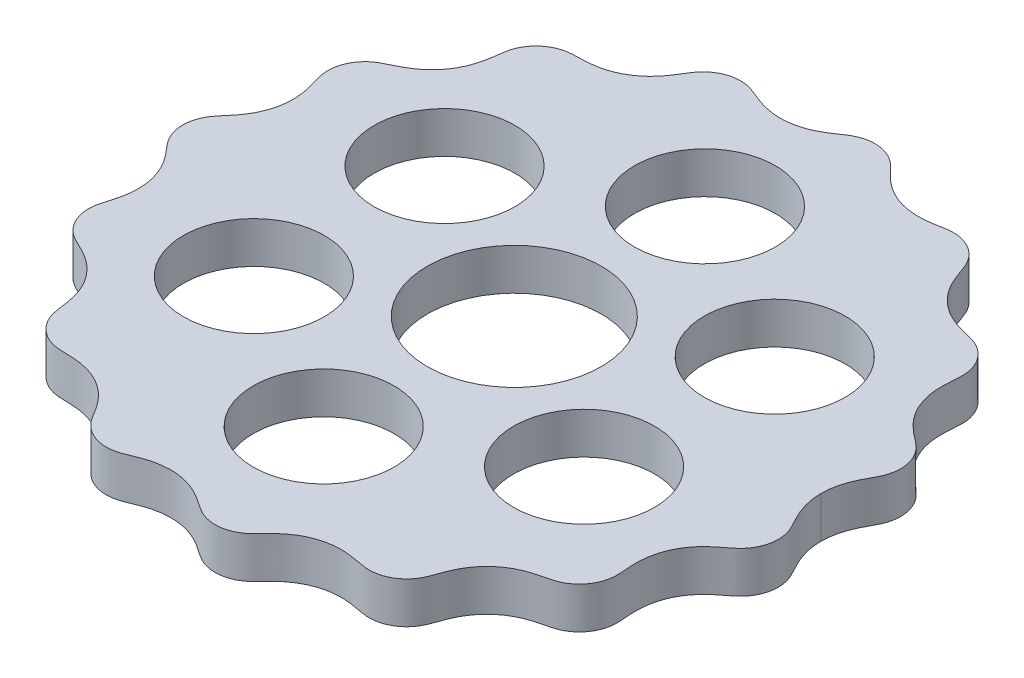
SolidWorks part; units mm, degrees
ref_plane "Front Plane" through (0, 0, 0) normal (0, 0, 1) x (1, 0, 0)
ref_plane "Top Plane" through (0, 0, 0) normal (0, 1, 0) x (1, 0, 0)
ref_plane "Right Plane" through (0, 0, 0) normal (1, 0, 0) x (0, 0, -1)
sketch "Sketch1" plane through (0, 0, 0) normal (0, 1, 0) x (1, 0, 0)
  circle A0 centre (0, 0) radius 10.5
  circle A1 centre (0, 0) radius 23 construction
  circle A2 centre (0, 23) radius 8.5
  circle A3 centre (19.9186, 11.5) radius 8.5
  circle A4 centre (19.9186, -11.5) radius 8.5
  circle A5 centre (0, -23) radius 8.5
  circle A6 centre (-19.9186, -11.5) radius 8.5
  circle A7 centre (-19.9186, 11.5) radius 8.5
  spline S0 degree 4 poles (38.6756, 9.5405) (38.7869, 9.3354) (38.9807, 8.9098) (39.18, 8.2438) (39.2638, 7.3275) (39.17, 6.4698) (38.9321, 5.7015) (38.5995, 5.0253) (38.2553, 4.4109) (37.9563, 3.8443) (37.7129, 3.322) (37.522, 2.8468) (37.3939, 2.4766) (37.2981, 2.1548) (37.2278, 1.884) (37.1776, 1.6659) (37.1334, 1.4465) (37.0953, 1.226) (37.0635, 1.0045) (37.0411, 0.8091) (37.0259, 0.6435) (37.0159, 0.5055) (37.0095, 0.392) (37.0035, 0.2438) (36.9999, 0.079) (36.9994, -0.0361) (37.0025, -0.21) (37.0079, -0.366) (37.0181, -0.5474) (37.0358, -0.7626) (37.0623, -1.0007) (37.0996, -1.2541) (37.1417, -1.4901) (37.1867, -1.7077) (37.276, -2.0862) (37.4326, -2.6197) (37.6503, -3.1917) (37.9334, -3.7956) (38.206, -4.3157) (38.4505, -4.7606) (38.7069, -5.2352) (38.9418, -5.7567) (39.1379, -6.3788) (39.248, -7.1039) (39.2286, -7.94) (39.0193, -8.8558) (38.5776, -9.8235) (37.821, -10.7544) (36.8481, -11.435) (35.9255, -12.1707) (35.1552, -12.9314) (34.5438, -13.6951) (33.8952, -14.742) (33.4284, -15.8904) (33.1613, -17.1041) (33.0908, -18.2767) (33.1179, -19.1348) (33.1846, -19.9227) (33.2426, -20.6446) (33.2196, -21.4379) (33.0363, -22.2817) (32.6622, -23.1285) (32.0787, -23.9264) (31.2705, -24.6475) (30.2129, -25.1958) (29.0562, -25.4259) (27.9212, -25.7148) (26.9129, -26.088) (26.0467, -26.5265) (25.2315, -27.0702) (24.4863, -27.7162) (23.8232, -28.4568) (23.2548, -29.2804) (22.819, -30.1054) (22.4892, -30.9045) (22.2262, -31.656) (21.9863, -32.3444) (21.6457, -33.0672) (21.1369, -33.7721) (20.4446, -34.4052) (19.5735, -34.9081) (18.6791, -35.1912) (17.8142, -35.2793) (17.018, -35.2129) (16.3018, -35.0765) (15.5195, -34.9284) (14.6625, -34.8147) (13.4804, -34.7697) (12.2411, -34.9196) (11.052, -35.2755) (9.9494, -35.8202) (9.1364, -36.3513) (8.3091, -37.0378) (7.4914, -37.8764) (6.7137, -38.763) (5.7101, -39.4048) (4.6815, -39.7442) (3.6987, -39.8506) (2.7784, -39.7512) (1.9559, -39.488) (1.2575, -39.1113) (0.6613, -38.7001) (0.0122, -38.2484) (-0.7173, -37.7958) (-1.768, -37.2706) (-2.9527, -36.8951) (-4.1807, -36.7251) (-5.4116, -36.7634) (-6.3787, -36.9109) (-7.4226, -37.1978) (-8.5211, -37.6287) (-9.5969, -38.1313) (-10.7814, -38.3206) (-11.8653, -38.2177) (-12.81, -37.9179) (-13.7654, -37.3701) (-14.6397, -36.51) (-15.225, -35.4471) (-15.8752, -34.4321) (-16.7227, -33.382) (-17.6452, -32.5494) (-18.6953, -31.8812) (-19.8393, -31.4031) (-20.7931, -31.1347) (-21.8817, -30.9645) (-23.0854, -30.9087) (-24.2988, -30.9334) (-25.4807, -30.6062) (-26.4329, -30.0527) (-27.1648, -29.3844) (-27.7959, -28.4973) (-28.2242, -27.3768) (-28.3269, -26.1938) (-28.503, -25.027) (-28.7764, -23.9796) (-29.1322, -23.0683) (-29.7145, -21.9831) (-30.4757, -21.0047) (-31.3933, -20.1664) (-32.3735, -19.5191) (-33.1302, -19.1136) (-33.8459, -18.7774) (-34.5001, -18.4667) (-35.1756, -18.0501) (-35.8147, -17.4694) (-36.361, -16.7221) (-36.7603, -15.8178) (-36.9806, -14.7573) (-36.9266, -13.5673) (-36.5476, -12.4504) (-36.2302, -11.323) (-36.0493, -10.2632) (-35.996, -9.2938) (-36.0592, -8.316) (-36.2461, -7.3476) (-36.5559, -6.4031) (-36.985, -5.499) (-37.4816, -4.7092) (-38.0086, -4.024) (-38.5281, -3.4205) (-39.0041, -2.8683) (-39.353, -2.3666) (-39.5782, -1.9309) (-39.7176, -1.5888) (-39.7983, -1.3525) (-39.8659, -1.1123) (-39.9132, -0.899) (-39.9453, -0.714) (-39.9664, -0.5608) (-39.98, -0.4381) (-39.9901, -0.3108) (-39.9969, -0.1759) (-40.0009, -0.0264) (-39.9998, 0.101) (-39.9919, 0.3019) (-39.9779, 0.461) (-39.962, 0.5936) (-39.9468, 0.7) (-39.9245, 0.8336) (-39.8928, 0.9931) (-39.8356, 1.2296) (-39.7321, 1.5628) (-39.5698, 1.9581) (-39.3263, 2.4015) (-39.0212, 2.8342) (-38.6301, 3.3062) (-38.1713, 3.8306) (-37.748, 4.3543) (-37.3751, 4.8861) (-37.0367, 5.4401) (-36.6355, 6.2077) (-36.2169, 7.3272) (-36.0304, 8.4018) (-36.0089, 9.2689) (-36.0283, 9.7011) knots 0 0 0 0 0 0.006139 0.012278 0.018165 0.024053 0.028687 0.033322 0.037957 0.042591 0.045535 0.048479 0.051424 0.052896 0.054368 0.05584 0.057312 0.058784 0.060256 0.061728 0.062464 0.0632 0.063936 0.064672 0.066144 0.067103 0.068061 0.06902 0.069978 0.071895 0.073812 0.075274 0.076735 0.078197 0.079659 0.085505 0.091352 0.094275 0.097198 0.100954 0.104711 0.108467 0.112223 0.11807 0.123916 0.130339 0.136761 0.145879 0.154997 0.161421 0.167846 0.17427 0.180694 0.193737 0.200258 0.206779 0.211542 0.216304 0.221067 0.225829 0.232349 0.238869 0.245245 0.251622 0.260677 0.269731 0.27611 0.282488 0.288866 0.295244 0.301811 0.308378 0.314945 0.321512 0.326307 0.331102 0.335897 0.340691 0.347256 0.353821 0.360386 0.366951 0.371745 0.37654 0.381335 0.38613 0.392697 0.399264 0.412398 0.418776 0.425154 0.431532 0.437911 0.446965 0.45602 0.462396 0.468773 0.475293 0.481813 0.486575 0.491338 0.4961 0.500863 0.507384 0.513905 0.526948 0.533372 0.539796 0.54622 0.552645 0.561763 0.570881 0.577303 0.583726 0.59023 0.596734 0.606103 0.615471 0.621978 0.628484 0.641498 0.648004 0.654511 0.661018 0.667524 0.676893 0.686261 0.692765 0.699269 0.705692 0.712114 0.721232 0.730351 0.736775 0.743199 0.749623 0.756047 0.76909 0.775611 0.782133 0.786895 0.791658 0.79642 0.801182 0.807702 0.814222 0.820599 0.826976 0.83603 0.845085 0.851463 0.857841 0.864219 0.870597 0.877164 0.883732 0.890299 0.896866 0.90166 0.906455 0.91125 0.916045 0.917686 0.919327 0.920968 0.922609 0.924251 0.925071 0.925892 0.926712 0.927533 0.928354 0.929174 0.930597 0.93202 0.932732 0.933444 0.934155 0.934867 0.93629 0.937713 0.940559 0.944036 0.947513 0.950991 0.954468 0.960159 0.965851 0.968697 0.971542 0.977234 0.988617 1 1 1 1 1 construction
  spline S1 degree 4 poles (37, 0) (37, -0.0314) (37.0005, -0.095) (37.0025, -0.21) (37.0079, -0.366) (37.0181, -0.5474) (37.0358, -0.7626) (37.0623, -1.0007) (37.0996, -1.2541) (37.1417, -1.4901) (37.1867, -1.7077) (37.276, -2.0862) (37.4326, -2.6197) (37.6503, -3.1917) (37.9334, -3.7956) (38.206, -4.3157) (38.4505, -4.7606) (38.7069, -5.2352) (38.9418, -5.7567) (39.1379, -6.3788) (39.248, -7.1039) (39.2286, -7.94) (39.0193, -8.8558) (38.5776, -9.8235) (37.821, -10.7544) (36.8481, -11.435) (35.9255, -12.1707) (35.1552, -12.9314) (34.5438, -13.6951) (33.8952, -14.742) (33.4284, -15.8904) (33.1613, -17.1041) (33.0908, -18.2767) (33.1179, -19.1348) (33.1846, -19.9227) (33.2426, -20.6446) (33.2196, -21.4379) (33.0363, -22.2817) (32.6622, -23.1285) (32.0787, -23.9264) (31.2705, -24.6475) (30.2129, -25.1958) (29.0562, -25.4259) (27.9212, -25.7148) (26.9129, -26.088) (26.0467, -26.5265) (25.2315, -27.0702) (24.4863, -27.7162) (23.8232, -28.4568) (23.2548, -29.2804) (22.819, -30.1054) (22.4892, -30.9045) (22.2262, -31.656) (21.9863, -32.3444) (21.6457, -33.0672) (21.1369, -33.7721) (20.4446, -34.4052) (19.5735, -34.9081) (18.6791, -35.1912) (17.8142, -35.2793) (17.018, -35.2129) (16.3018, -35.0765) (15.5195, -34.9284) (14.6625, -34.8147) (13.4804, -34.7697) (12.2411, -34.9196) (11.052, -35.2755) (9.9494, -35.8202) (9.1364, -36.3513) (8.3091, -37.0378) (7.4914, -37.8764) (6.7137, -38.763) (5.7101, -39.4048) (4.6815, -39.7442) (3.6987, -39.8506) (2.7784, -39.7512) (1.9559, -39.488) (1.2575, -39.1113) (0.6613, -38.7001) (0.0122, -38.2484) (-0.7173, -37.7958) (-1.768, -37.2706) (-2.9527, -36.8951) (-4.1807, -36.7251) (-5.4116, -36.7634) (-6.3787, -36.9109) (-7.4226, -37.1978) (-8.5211, -37.6287) (-9.5969, -38.1313) (-10.7814, -38.3206) (-11.8653, -38.2177) (-12.81, -37.9179) (-13.7654, -37.3701) (-14.6397, -36.51) (-15.225, -35.4471) (-15.8752, -34.4321) (-16.7227, -33.382) (-17.6452, -32.5494) (-18.6953, -31.8812) (-19.8393, -31.4031) (-20.7931, -31.1347) (-21.8817, -30.9645) (-23.0854, -30.9087) (-24.2988, -30.9334) (-25.4807, -30.6062) (-26.4329, -30.0527) (-27.1648, -29.3844) (-27.7959, -28.4973) (-28.2242, -27.3768) (-28.3269, -26.1938) (-28.503, -25.027) (-28.7764, -23.9796) (-29.1322, -23.0683) (-29.7145, -21.9831) (-30.4757, -21.0047) (-31.3933, -20.1664) (-32.3735, -19.5191) (-33.1302, -19.1136) (-33.8459, -18.7774) (-34.5001, -18.4667) (-35.1756, -18.0501) (-35.8147, -17.4694) (-36.361, -16.7221) (-36.7603, -15.8178) (-36.9806, -14.7573) (-36.9266, -13.5673) (-36.5476, -12.4504) (-36.2302, -11.323) (-36.0493, -10.2632) (-35.996, -9.2938) (-36.0592, -8.316) (-36.2461, -7.3476) (-36.5559, -6.4031) (-36.985, -5.499) (-37.4816, -4.7092) (-38.0086, -4.024) (-38.5281, -3.4205) (-39.0041, -2.8683) (-39.353, -2.3666) (-39.5782, -1.9309) (-39.7176, -1.5888) (-39.7983, -1.3525) (-39.8659, -1.1123) (-39.9132, -0.899) (-39.9453, -0.714) (-39.9664, -0.5608) (-39.98, -0.4381) (-39.9901, -0.3108) (-39.9969, -0.1759) (-39.9994, -0.0812) (-40, -0.0269) (-40, 0) knots 0.066144 0.066144 0.066144 0.066144 0.066144 0.067103 0.068061 0.06902 0.069978 0.071895 0.073812 0.075274 0.076735 0.078197 0.079659 0.085505 0.091352 0.094275 0.097198 0.100954 0.104711 0.108467 0.112223 0.11807 0.123916 0.130339 0.136761 0.145879 0.154997 0.161421 0.167846 0.17427 0.180694 0.193737 0.200258 0.206779 0.211542 0.216304 0.221067 0.225829 0.232349 0.238869 0.245245 0.251622 0.260677 0.269731 0.27611 0.282488 0.288866 0.295244 0.301811 0.308378 0.314945 0.321512 0.326307 0.331102 0.335897 0.340691 0.347256 0.353821 0.360386 0.366951 0.371745 0.37654 0.381335 0.38613 0.392697 0.399264 0.412398 0.418776 0.425154 0.431532 0.437911 0.446965 0.45602 0.462396 0.468773 0.475293 0.481813 0.486575 0.491338 0.4961 0.500863 0.507384 0.513905 0.526948 0.533372 0.539796 0.54622 0.552645 0.561763 0.570881 0.577303 0.583726 0.59023 0.596734 0.606103 0.615471 0.621978 0.628484 0.641498 0.648004 0.654511 0.661018 0.667524 0.676893 0.686261 0.692765 0.699269 0.705692 0.712114 0.721232 0.730351 0.736775 0.743199 0.749623 0.756047 0.76909 0.775611 0.782133 0.786895 0.791658 0.79642 0.801182 0.807702 0.814222 0.820599 0.826976 0.83603 0.845085 0.851463 0.857841 0.864219 0.870597 0.877164 0.883732 0.890299 0.896866 0.90166 0.906455 0.91125 0.916045 0.917686 0.919327 0.920968 0.922609 0.924251 0.925071 0.925892 0.926712 0.927533 0.928354 0.929174 0.929174 0.929174 0.929174 0.929174
  spline S2 degree 4 poles (-36.0283, -9.7011) (-36.0089, -9.2689) (-36.025, -8.6185) (-36.1423, -7.7571) (-36.4452, -6.7165) (-36.7773, -5.9157) (-37.1923, -5.1548) (-37.6189, -4.528) (-38.0202, -4.0177) (-38.3849, -3.5864) (-38.6992, -3.2229) (-38.979, -2.8851) (-39.2119, -2.5638) (-39.3869, -2.2834) (-39.514, -2.0514) (-39.6452, -1.7744) (-39.7518, -1.4995) (-39.8356, -1.2297) (-39.8991, -0.9667) (-39.9398, -0.7534) (-39.9703, -0.5412) (-39.9907, -0.329) (-39.9998, -0.1024) (-40.0009, 0.0274) (-39.9969, 0.174) (-39.9901, 0.3085) (-39.98, 0.4378) (-39.9664, 0.5616) (-39.9495, 0.6838) (-39.9292, 0.8064) (-39.9056, 0.9291) (-39.8785, 1.0511) (-39.8405, 1.2024) (-39.7882, 1.382) (-39.7175, 1.5887) (-39.6127, 1.8466) (-39.4787, 2.1231) (-39.3107, 2.4141) (-39.1049, 2.7153) (-38.8813, 3.0032) (-38.6471, 3.2825) (-38.3498, 3.6277) (-37.9529, 4.0962) (-37.4817, 4.7093) (-36.9849, 5.4989) (-36.556, 6.4033) (-36.1702, 7.5783) (-35.9868, 8.7988) (-36.0091, 10.0244) (-36.2006, 11.152) (-36.4085, 11.955) (-36.6307, 12.6803) (-36.8216, 13.3417) (-36.9923, 14.3318) (-36.9049, 15.4222) (-36.5044, 16.5243) (-35.815, 17.4697) (-35.1754, 18.05) (-34.5001, 18.4666) (-33.846, 18.7777) (-32.9056, 19.2181) (-31.7252, 19.8872) (-30.4396, 20.9666) (-29.2852, 22.5861) (-28.6866, 24.1372) (-28.4341, 25.439) (-28.3116, 26.4395) (-28.2186, 27.1266) (-28.0361, 27.8709) (-27.6947, 28.6385) (-27.1647, 29.385) (-26.4334, 30.0526) (-25.6346, 30.5161) (-24.8231, 30.7888) (-24.0469, 30.8992) (-23.3347, 30.9203) (-22.3064, 30.9378) (-20.9635, 31.0586) (-19.3449, 31.507) (-17.6134, 32.5067) (-16.4158, 33.6842) (-15.6397, 34.7868) (-15.1104, 35.6686) (-14.7361, 36.2748) (-14.2524, 36.8918) (-13.6104, 37.4583) (-12.8096, 37.9183) (-11.8658, 38.2178) (-10.9543, 38.3035) (-10.1188, 38.2154) (-9.383, 38.0014) (-8.7414, 37.7383) (-7.8138, 37.3442) (-6.5601, 36.912) (-4.9175, 36.6548) (-2.9379, 36.8448) (-1.3603, 37.4184) (-0.1906, 38.1061) (0.661, 38.7003) (1.2575, 39.1113) (1.9559, 39.4878) (2.7783, 39.7515) (3.9418, 39.8759) (5.0965, 39.6717) (6.0845, 39.2022) (6.8565, 38.5593) (7.3339, 38.0633) (7.8509, 37.5082) (8.4424, 36.9267) (9.3231, 36.1969) (10.5884, 35.4356) (11.9992, 34.9487) (13.4803, 34.7698) (14.6625, 34.8147) (15.5194, 34.9284) (16.3018, 35.0765) (17.0179, 35.2129) (17.8142, 35.2793) (18.6791, 35.1911) (19.5735, 34.9082) (20.4445, 34.4052) (21.137, 33.7722) (21.5918, 33.1415) (21.8696, 32.5926) (22.0759, 32.0862) (22.2266, 31.6561) (22.3766, 31.2261) (22.5937, 30.6514) (22.8615, 30.0249) (23.2551, 29.2802) (23.8228, 28.4571) (24.6491, 27.5346) (25.8025, 26.6152) (27.2181, 25.9053) (28.8176, 25.4727) (30.4528, 25.1488) (31.6988, 24.3833) (32.5609, 23.3518) (33.0376, 22.2818) (33.2189, 21.4379) (33.243, 20.6446) (33.1848, 19.9227) (33.0963, 18.888) (33.0853, 17.5312) (33.3775, 15.8781) (34.2027, 14.0687) (35.2468, 12.7747) (36.2479, 11.9052) (37.0531, 11.2989) (37.6016, 10.8748) (38.155, 10.3445) (38.649, 9.665) (39.0305, 8.8328) (39.243, 7.8658) (39.2451, 6.9422) (39.0753, 6.1031) (38.7832, 5.3754) (38.4446, 4.7486) (38.1266, 4.173) (37.8549, 3.634) (37.633, 3.1317) (37.4786, 2.7272) (37.3626, 2.3747) (37.2774, 2.0775) (37.2164, 1.8379) (37.1626, 1.5964) (37.1163, 1.3536) (37.0774, 1.1094) (37.0502, 0.8937) (37.0316, 0.7109) (37.0194, 0.5584) (37.0116, 0.4331) (37.0042, 0.2696) (36.9994, 0.0658) (36.9993, -0.087) (37.0071, -0.3742) (37.0226, -0.616) (37.0458, -0.8587) (37.0767, -1.1038) (37.1247, -1.4076) (37.1852, -1.7092) (37.2578, -2.0082) (37.3591, -2.3632) (37.4739, -2.7141) (37.627, -3.1167) (37.8469, -3.6171) (38.1165, -4.154) (38.4326, -4.7273) (38.7709, -5.3508) (39.0661, -6.0733) (39.2414, -6.9072) (39.2472, -7.9128) (39.0566, -8.7198) (38.8323, -9.2517) (38.6756, -9.5405) knots 0 0 0 0 0 0.011383 0.017074 0.022766 0.028458 0.034149 0.039841 0.042687 0.045532 0.049009 0.052487 0.054225 0.055964 0.057702 0.059441 0.062287 0.06371 0.065133 0.066556 0.06798 0.069403 0.070826 0.071646 0.072467 0.073288 0.074108 0.074929 0.075749 0.07657 0.077391 0.078211 0.079032 0.080673 0.082314 0.083955 0.086353 0.08875 0.091148 0.093545 0.095942 0.09834 0.103134 0.109701 0.116269 0.122836 0.129403 0.142159 0.148537 0.154915 0.159443 0.16397 0.168497 0.173024 0.185778 0.192298 0.198818 0.20358 0.208342 0.213105 0.217867 0.23091 0.243953 0.256801 0.269649 0.274209 0.278768 0.283327 0.287886 0.294308 0.300731 0.307235 0.313739 0.318423 0.323107 0.327792 0.332476 0.345489 0.358502 0.371516 0.384529 0.389213 0.393897 0.398582 0.403266 0.40977 0.416274 0.422697 0.429119 0.433678 0.438237 0.442796 0.447355 0.460204 0.473052 0.486095 0.499137 0.5039 0.508662 0.513425 0.518187 0.524707 0.531227 0.54398 0.548508 0.553035 0.557562 0.56209 0.568468 0.574846 0.587602 0.600736 0.607303 0.613871 0.618665 0.62346 0.628255 0.633049 0.639614 0.646179 0.652744 0.659309 0.664104 0.666501 0.668898 0.673693 0.67609 0.678488 0.685055 0.691622 0.698189 0.704756 0.717512 0.730269 0.739323 0.748378 0.761131 0.767651 0.774171 0.778933 0.783696 0.788458 0.793221 0.806263 0.819306 0.832154 0.845003 0.849562 0.854121 0.85868 0.863239 0.869662 0.876084 0.882588 0.889092 0.893777 0.898461 0.903145 0.907829 0.911083 0.914336 0.917589 0.919216 0.920842 0.922469 0.924096 0.925722 0.927349 0.928976 0.929789 0.930602 0.931416 0.932229 0.933856 0.935474 0.937093 0.938711 0.94033 0.941948 0.943567 0.946804 0.948422 0.950041 0.953278 0.956515 0.959752 0.964416 0.96908 0.973744 0.978408 0.984882 0.991355 1 1 1 1 1 construction
  spline S3 degree 4 poles (-40, 0) (-40, 0.0269) (-39.9994, 0.0811) (-39.9969, 0.174) (-39.9901, 0.3085) (-39.98, 0.4378) (-39.9664, 0.5616) (-39.9495, 0.6838) (-39.9292, 0.8064) (-39.9056, 0.9291) (-39.8785, 1.0511) (-39.8405, 1.2024) (-39.7882, 1.382) (-39.7175, 1.5887) (-39.6127, 1.8466) (-39.4787, 2.1231) (-39.3107, 2.4141) (-39.1049, 2.7153) (-38.8813, 3.0032) (-38.6471, 3.2825) (-38.3498, 3.6277) (-37.9529, 4.0962) (-37.4817, 4.7093) (-36.9849, 5.4989) (-36.556, 6.4033) (-36.1702, 7.5783) (-35.9868, 8.7988) (-36.0091, 10.0244) (-36.2006, 11.152) (-36.4085, 11.955) (-36.6307, 12.6803) (-36.8216, 13.3417) (-36.9923, 14.3318) (-36.9049, 15.4222) (-36.5044, 16.5243) (-35.815, 17.4697) (-35.1754, 18.05) (-34.5001, 18.4666) (-33.846, 18.7777) (-32.9056, 19.2181) (-31.7252, 19.8872) (-30.4396, 20.9666) (-29.2852, 22.5861) (-28.6866, 24.1372) (-28.4341, 25.439) (-28.3116, 26.4395) (-28.2186, 27.1266) (-28.0361, 27.8709) (-27.6947, 28.6385) (-27.1647, 29.385) (-26.4334, 30.0526) (-25.6346, 30.5161) (-24.8231, 30.7888) (-24.0469, 30.8992) (-23.3347, 30.9203) (-22.3064, 30.9378) (-20.9635, 31.0586) (-19.3449, 31.507) (-17.6134, 32.5067) (-16.4158, 33.6842) (-15.6397, 34.7868) (-15.1104, 35.6686) (-14.7361, 36.2748) (-14.2524, 36.8918) (-13.6104, 37.4583) (-12.8096, 37.9183) (-11.8658, 38.2178) (-10.9543, 38.3035) (-10.1188, 38.2154) (-9.383, 38.0014) (-8.7414, 37.7383) (-7.8138, 37.3442) (-6.5601, 36.912) (-4.9175, 36.6548) (-2.9379, 36.8448) (-1.3603, 37.4184) (-0.1906, 38.1061) (0.661, 38.7003) (1.2575, 39.1113) (1.9559, 39.4878) (2.7783, 39.7515) (3.9418, 39.8759) (5.0965, 39.6717) (6.0845, 39.2022) (6.8565, 38.5593) (7.3339, 38.0633) (7.8509, 37.5082) (8.4424, 36.9267) (9.3231, 36.1969) (10.5884, 35.4356) (11.9992, 34.9487) (13.4803, 34.7698) (14.6625, 34.8147) (15.5194, 34.9284) (16.3018, 35.0765) (17.0179, 35.2129) (17.8142, 35.2793) (18.6791, 35.1911) (19.5735, 34.9082) (20.4445, 34.4052) (21.137, 33.7722) (21.5918, 33.1415) (21.8696, 32.5926) (22.0759, 32.0862) (22.2266, 31.6561) (22.3766, 31.2261) (22.5937, 30.6514) (22.8615, 30.0249) (23.2551, 29.2802) (23.8228, 28.4571) (24.6491, 27.5346) (25.8025, 26.6152) (27.2181, 25.9053) (28.8176, 25.4727) (30.4528, 25.1488) (31.6988, 24.3833) (32.5609, 23.3518) (33.0376, 22.2818) (33.2189, 21.4379) (33.243, 20.6446) (33.1848, 19.9227) (33.0963, 18.888) (33.0853, 17.5312) (33.3775, 15.8781) (34.2027, 14.0687) (35.2468, 12.7747) (36.2479, 11.9052) (37.0531, 11.2989) (37.6016, 10.8748) (38.155, 10.3445) (38.649, 9.665) (39.0305, 8.8328) (39.243, 7.8658) (39.2451, 6.9422) (39.0753, 6.1031) (38.7832, 5.3754) (38.4446, 4.7486) (38.1266, 4.173) (37.8549, 3.634) (37.633, 3.1317) (37.4786, 2.7272) (37.3626, 2.3747) (37.2774, 2.0775) (37.2164, 1.8379) (37.1626, 1.5964) (37.1163, 1.3536) (37.0774, 1.1094) (37.0502, 0.8937) (37.0316, 0.7109) (37.0194, 0.5584) (37.0116, 0.4331) (37.0042, 0.2696) (37.001, 0.1335) (37, 0.0534) (37, 0) knots 0.070826 0.070826 0.070826 0.070826 0.070826 0.071646 0.072467 0.073288 0.074108 0.074929 0.075749 0.07657 0.077391 0.078211 0.079032 0.080673 0.082314 0.083955 0.086353 0.08875 0.091148 0.093545 0.095942 0.09834 0.103134 0.109701 0.116269 0.122836 0.129403 0.142159 0.148537 0.154915 0.159443 0.16397 0.168497 0.173024 0.185778 0.192298 0.198818 0.20358 0.208342 0.213105 0.217867 0.23091 0.243953 0.256801 0.269649 0.274209 0.278768 0.283327 0.287886 0.294308 0.300731 0.307235 0.313739 0.318423 0.323107 0.327792 0.332476 0.345489 0.358502 0.371516 0.384529 0.389213 0.393897 0.398582 0.403266 0.40977 0.416274 0.422697 0.429119 0.433678 0.438237 0.442796 0.447355 0.460204 0.473052 0.486095 0.499137 0.5039 0.508662 0.513425 0.518187 0.524707 0.531227 0.54398 0.548508 0.553035 0.557562 0.56209 0.568468 0.574846 0.587602 0.600736 0.607303 0.613871 0.618665 0.62346 0.628255 0.633049 0.639614 0.646179 0.652744 0.659309 0.664104 0.666501 0.668898 0.673693 0.67609 0.678488 0.685055 0.691622 0.698189 0.704756 0.717512 0.730269 0.739323 0.748378 0.761131 0.767651 0.774171 0.778933 0.783696 0.788458 0.793221 0.806263 0.819306 0.832154 0.845003 0.849562 0.854121 0.85868 0.863239 0.869662 0.876084 0.882588 0.889092 0.893777 0.898461 0.903145 0.907829 0.911083 0.914336 0.917589 0.919216 0.920842 0.922469 0.924096 0.925722 0.927349 0.928976 0.929789 0.930602 0.931416 0.932229 0.933856 0.933856 0.933856 0.933856 0.933856
  point P1 (-90.9916, 26.8684)
  point P6 (-87.702, -9.1349)
  point P24 (0, 0)
  dimension "D1" = 21
  dimension "D2" = 17
  dimension "D4" = 46
  dimension "D3" = 6
extrude "Boss-Extrude1" add sketch "Sketch1" along normal blind 5
